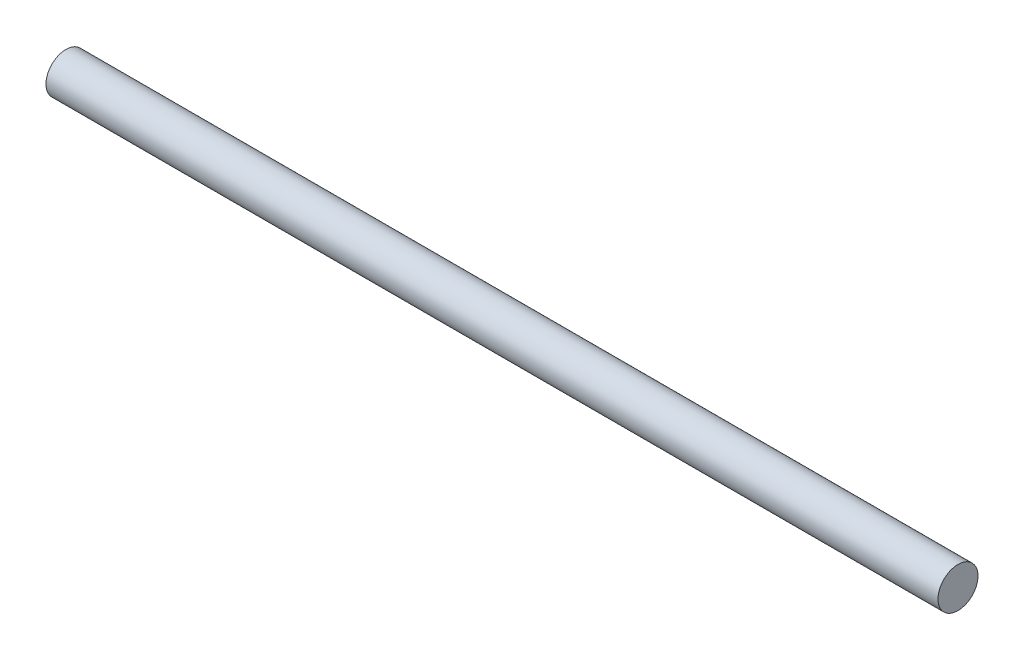
SolidWorks part; units mm, degrees
ref_plane "Front Plane" through (0, 0, 0) normal (0, 0, 1) x (1, 0, 0)
ref_plane "Top Plane" through (0, 0, 0) normal (0, 1, 0) x (1, 0, 0)
ref_plane "Right Plane" through (0, 0, 0) normal (1, 0, 0) x (0, 0, -1)
sketch "Sketch1" plane through (0, 0, 0) normal (1, 0, 0) x (0, 0, -1)
  circle A0 centre (0, 0) radius 1.75
  dimension "D1" = 3.5
extrude "Boss-Extrude1" add sketch "Sketch1" along normal blind 78
